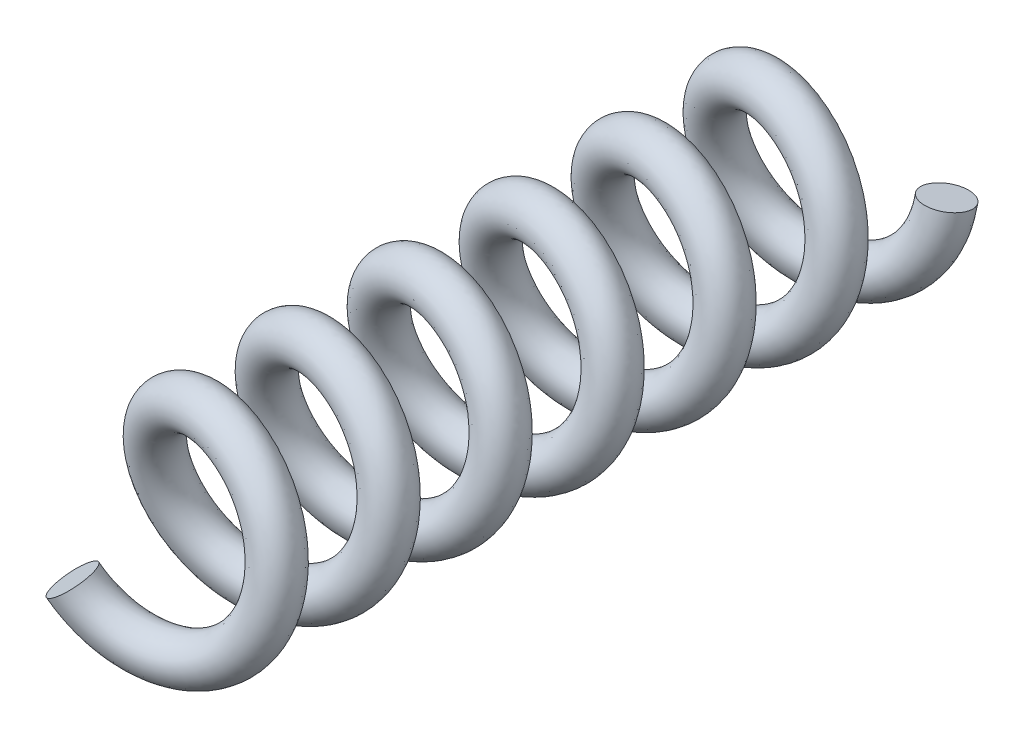
SolidWorks part; units mm, degrees
ref_plane "Front Plane" through (0, 0, 0) normal (0, 0, 1) x (1, 0, 0)
ref_plane "Top Plane" through (0, 0, 0) normal (0, 1, 0) x (1, 0, 0)
ref_plane "Right Plane" through (0, 0, 0) normal (1, 0, 0) x (0, 0, -1)
sketch "Sketch1" plane through (0, 0, 0) normal (0, 0, 1) x (1, 0, 0)
  circle A0 centre (0, 0) radius 4
curve "Helix/Spiral1" pitch 5 height 32 turns 6.4
ref_plane "Plane1" through (4, 0, 0) normal (0, -0.9808, 0.1951) x (-1, 0, 0)
sketch "Sketch5" plane through (4, 0, 0) normal (0, -0.9808, 0.1951) x (-1, 0, 0)
  circle A0 centre (0.1113, 0) radius 1
sweep "Sweep1" add profiles "Sketch5" path "Helix/Spiral1"
